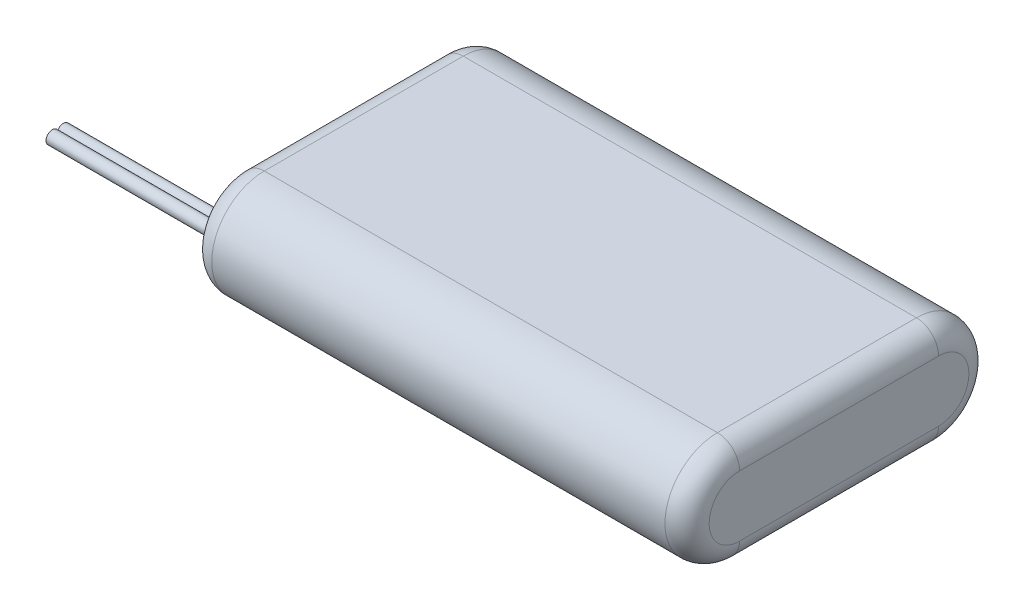
SolidWorks part; units mm, degrees
ref_plane "Front Plane" through (0, 0, 0) normal (0, 0, 1) x (1, 0, 0)
ref_plane "Top Plane" through (0, 0, 0) normal (0, 1, 0) x (1, 0, 0)
ref_plane "Right Plane" through (0, 0, 0) normal (1, 0, 0) x (0, 0, -1)
sketch "Sketch1" plane through (0, 0, 0) normal (1, 0, 0) x (0, 0, -1)
  line L0 (-9, 0) -> (9, 0) construction
  line L1 (-9, 4.75) -> (9, 4.75)
  line L2 (-9, -4.75) -> (9, -4.75)
  line L3 (-13.75, 0) -> (-9, 0) construction
  line L4 (9, 0) -> (13.75, 0) construction
  arc A0 (-9, 4.75) -> (-9, -4.75) centre (-9, 0) ccw
  arc A1 (9, -4.75) -> (9, 4.75) centre (9, 0) ccw
  point P3 (0, 0)
  dimension "D1" = 9.5
  dimension "D2" = 27.5
extrude "Boss-Extrude1" add sketch "Sketch1" along normal mid plane 45
fillet "Fillet1" radius 2 8 edges at (-22.5, 0, 13.75) (-22.5, 4.75, 0) (-22.5, 0, -13.75) (22.5, 4.75, 0) (22.5, 0, -13.75) (22.5, -4.75, 0) (22.5, 0, 13.75) (-22.5, -4.75, 0)
sketch "Sketch2" plane through (-22.5, 0, 0) normal (-1, 0, 0) x (0, 0, 1)
  line L0 (10.175, 0) -> (11.175, 0) construction
  line L1 (0, 0) -> (10.175, 0) construction
  line L2 (11.75, 0) -> (13.75, 0) construction
  arc A0 (10.675, 0.2839) -> (10.675, -0.2839) centre (10.175, 0) ccw
  arc A1 (10.675, -0.2839) -> (10.675, 0.2839) centre (11.175, 0) ccw
  arc A2 (9, -4.75) -> (9, 4.75) centre (9, 0) ccw construction
  dimension "D1" = 1.15
  dimension "D2" = 1
  dimension "D3" = 2
extrude "Boss-Extrude2" add sketch "Sketch2" along normal blind 15
